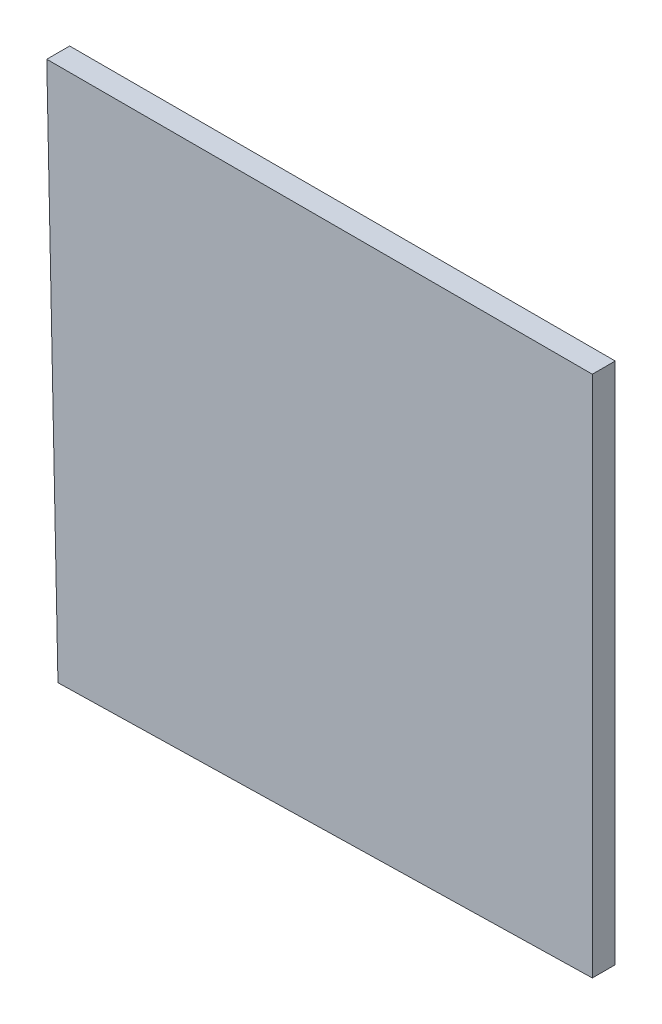
SolidWorks part; units mm, degrees
ref_plane "Plan de face" through (0, 0, 0) normal (0, 0, 1) x (1, 0, 0)
ref_plane "Plan de dessus" through (0, 0, 0) normal (0, 1, 0) x (1, 0, 0)
ref_plane "Plan de droite" through (0, 0, 0) normal (1, 0, 0) x (0, 0, -1)
sketch "Esquisse1" plane through (0, 0, 0) normal (0, 0, 1) x (1, 0, 0)
  line L0 (-103.5573, 82.6155) -> (134.6827, 82.6155)
  line L1 (134.6827, 82.6155) -> (134.6827, -145.7245)
  line L2 (134.6827, -145.7245) -> (-98.6673, -150.7345)
  line L3 (-98.6673, -150.7345) -> (-103.5573, 82.6155)
  dimension "D1" = 238.24
  dimension "D2" = 228.34
  dimension "D3" = 233.35
  dimension "D4" = 233.35
extrude "Boss.-Extru.1" add sketch "Esquisse1" along normal blind 10
sketch "Esquisse2" plane through (0, 0, 0) normal (0, 0, 1) x (1, 0, 0)
  line L0 (-79.3535, 68.8496) -> (-73.0257, -135.6364)
  line L1 (-73.0257, -135.6364) -> (112.4952, -129.8956)
  line L2 (112.4952, -129.8956) -> (115.4744, 68.8496)
  line L3 (115.4744, 68.8496) -> (-79.3535, 68.8496)
  dimension "D1" = 204.486
